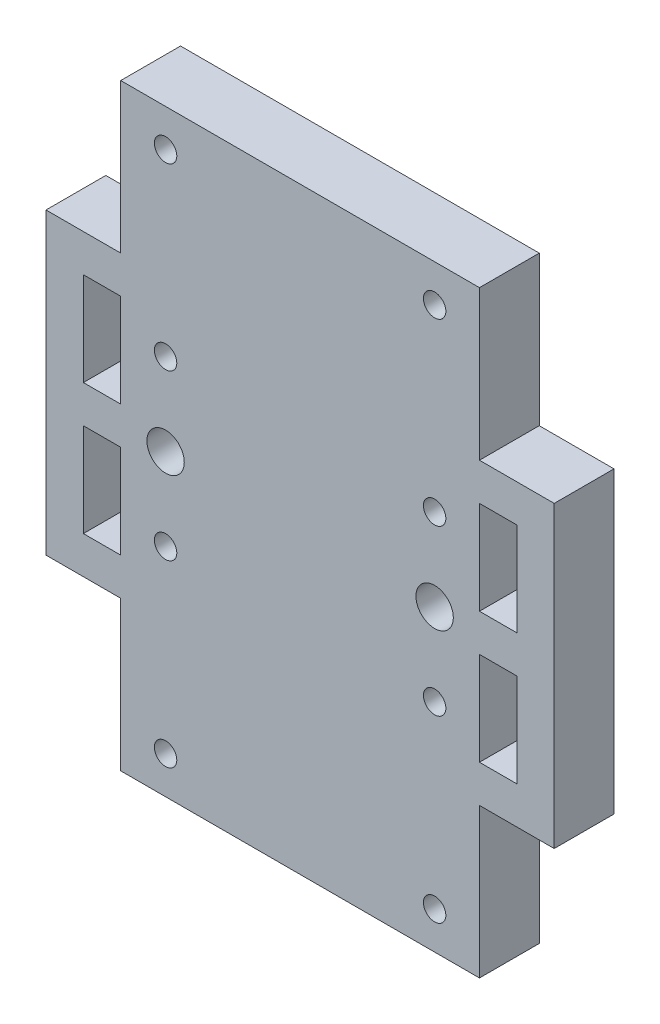
SolidWorks part; units mm, degrees
ref_plane "前视基准面" through (0, 0, 0) normal (0, 0, 1) x (1, 0, 0)
ref_plane "上视基准面" through (0, 0, 0) normal (0, 1, 0) x (1, 0, 0)
ref_plane "右视基准面" through (0, 0, 0) normal (1, 0, 0) x (0, 0, -1)
sketch "草图1" plane through (0, 0, 0) normal (0, 0, 1) x (1, 0, 0)
  line L0 (2.0625, -8.5938) -> (2.0625, 11.4062) construction
  line L1 (-45.9375, 31.4062) -> (2.0625, 31.4062)
  line L2 (-45.9375, 31.4062) -> (-45.9375, -48.5938)
  line L3 (-45.9375, -48.5938) -> (2.0625, -48.5938)
  line L4 (2.0625, 31.4062) -> (2.0625, -48.5938)
  line L5 (-21.9375, 31.4062) -> (-21.9375, -48.5938) construction
  line L6 (2.0625, 11.4062) -> (12.0625, 11.4063)
  line L7 (2.0625, 11.4062) -> (2.0625, -28.5937)
  line L8 (2.0625, -28.5937) -> (12.0625, -28.5937)
  line L9 (12.0625, 11.4063) -> (12.0625, -28.5937)
  line L10 (2.0625, 6.4063) -> (7.0625, 6.4063)
  line L11 (2.0625, 6.4063) -> (2.0625, -6.0937)
  line L12 (2.0625, -6.0937) -> (7.0625, -6.0937)
  line L13 (7.0625, 6.4063) -> (7.0625, -6.0937)
  line L14 (2.0625, -23.5937) -> (7.0625, -23.5937)
  line L15 (2.0625, -23.5937) -> (2.0625, -11.0937)
  line L16 (2.0625, -11.0937) -> (7.0625, -11.0937)
  line L17 (7.0625, -23.5937) -> (7.0625, -11.0937)
  line L18 (2.0625, 14.4062) -> (-3.9375, 14.4062) construction
  line L19 (-3.9375, 26.4062) -> (-3.9375, 2.4062)
  line L20 (-45.9375, -8.5937) -> (2.0625, -8.5938) construction
  line L21 (-45.9375, -6.0937) -> (-50.9375, -6.0937)
  line L22 (-50.9375, 6.4063) -> (-50.9375, -6.0937)
  line L23 (-45.9375, 6.4063) -> (-50.9375, 6.4063)
  line L24 (-45.9375, 6.4063) -> (-45.9375, -6.0937)
  line L25 (-45.9375, -11.0937) -> (-50.9375, -11.0937)
  line L26 (-50.9375, -23.5937) -> (-50.9375, -11.0937)
  line L27 (-45.9375, -23.5937) -> (-50.9375, -23.5937)
  line L28 (-45.9375, -23.5937) -> (-45.9375, -11.0937)
  line L29 (-45.9375, -28.5937) -> (-55.9375, -28.5937)
  line L30 (-55.9375, 11.4063) -> (-55.9375, -28.5937)
  line L31 (-45.9375, 11.4062) -> (-55.9375, 11.4063)
  line L32 (-45.9375, 11.4062) -> (-45.9375, -28.5937)
  circle A0 centre (-3.9375, 26.4062) radius 1.5
  circle A1 centre (-3.9375, 2.4062) radius 1.5
  circle A2 centre (-3.9375, -19.5938) radius 1.5
  circle A3 centre (-3.9375, -43.5938) radius 1.5
  circle A4 centre (-39.9375, -43.5938) radius 1.5
  circle A5 centre (-39.9375, -19.5938) radius 1.5
  circle A6 centre (-39.9375, 2.4062) radius 1.5
  circle A7 centre (-39.9375, 26.4062) radius 1.5
  point P9 (2.0625, 6.4063)
  point P10 (2.0625, -23.5937)
  point P21 (2.0625, 14.4062)
  point P27 (-3.9375, 14.4062)
  dimension "D1" = 80
  dimension "D2" = 48
  dimension "D3" = 20
  dimension "D4" = 40
  dimension "D5" = 10
  dimension "D6" = 5
  dimension "D7" = 5
  dimension "D8" = 12.5
  dimension "D9" = 5
  dimension "D10" = 12.5
  dimension "D11" = 5
  dimension "D12" = 17
  dimension "D13" = 6
  dimension "D14" = 24
extrude "凸台-拉伸1" add sketch "草图1" along normal blind 8
sketch "草图2" plane through (0, 0, 8) normal (0, 0, 1) x (1, 0, 0)
  line L0 (-45.9375, -11.0937) -> (-45.9375, -6.0937) construction
  line L1 (2.0625, -11.0937) -> (2.0625, -6.0937) construction
  line L2 (-45.9375, -8.5937) -> (2.0625, -8.5937) construction
  circle A0 centre (-39.9375, -8.5937) radius 2.5
  circle A1 centre (-3.9375, -8.5937) radius 2.5
  point P11 (-39.9375, -8.5937)
  point P13 (-3.9375, -8.5937)
  dimension "D1" = 6
  dimension "D2" = 6
extrude "切除-拉伸1" cut sketch "草图2" against normal blind 10
